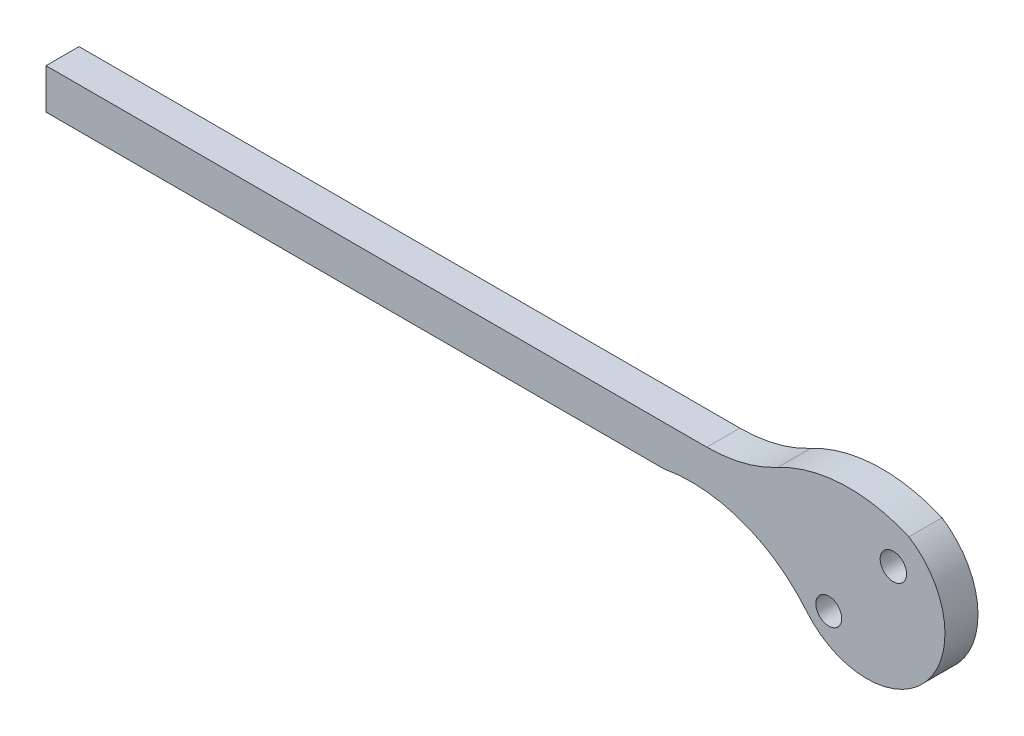
SolidWorks part; units mm, degrees
ref_plane "Front Plane" through (0, 0, 0) normal (0, 0, 1) x (1, 0, 0)
ref_plane "Top Plane" through (0, 0, 0) normal (0, 1, 0) x (1, 0, 0)
ref_plane "Right Plane" through (0, 0, 0) normal (1, 0, 0) x (0, 0, -1)
sketch "Sketch2" plane through (0, 0, 0) normal (0, 0, 1) x (1, 0, 0)
  line L0 (0, 0) -> (80.6834, 75.8568) construction
  line L1 (16.5538, 15.5635) -> (-110.4462, 15.5635) construction
  line L2 (-110.4462, 15.5635) -> (-110.4462, 7.8293) construction
  line L3 (-110.4462, 7.8293) -> (8.3275, 7.8293) construction
  line L4 (16.5538, 15.5635) -> (-110.4462, 15.5635)
  line L5 (-110.4462, 15.5635) -> (-110.4462, 7.8293)
  line L6 (-110.4462, 7.8293) -> (8.3275, 7.8293)
  arc A0 (55.4007, 20.0737) -> (35.7121, -2.1324) centre (47.3093, 7.4165) cw
  arc A1 (35.7121, -2.1324) -> (8.3275, 7.8293) centre (13.5784, -20.3566) ccw
  arc A2 (16.5538, 15.5635) -> (30.1576, 18.9927) centre (16.5538, 44.2622) ccw
  arc A3 (30.1576, 18.9927) -> (55.4007, 20.0737) centre (43.8951, -6.5251) cw
  circle A6 centre (52.4107, 13.6341) radius 2.54
  circle A10 centre (40, 0) radius 2.4892
  point P5 (8.3275, 7.8293)
  point P6 (16.5538, 15.5635)
extrude "Boss-Extrude4" add sketch "Sketch2" along normal blind 6.35
